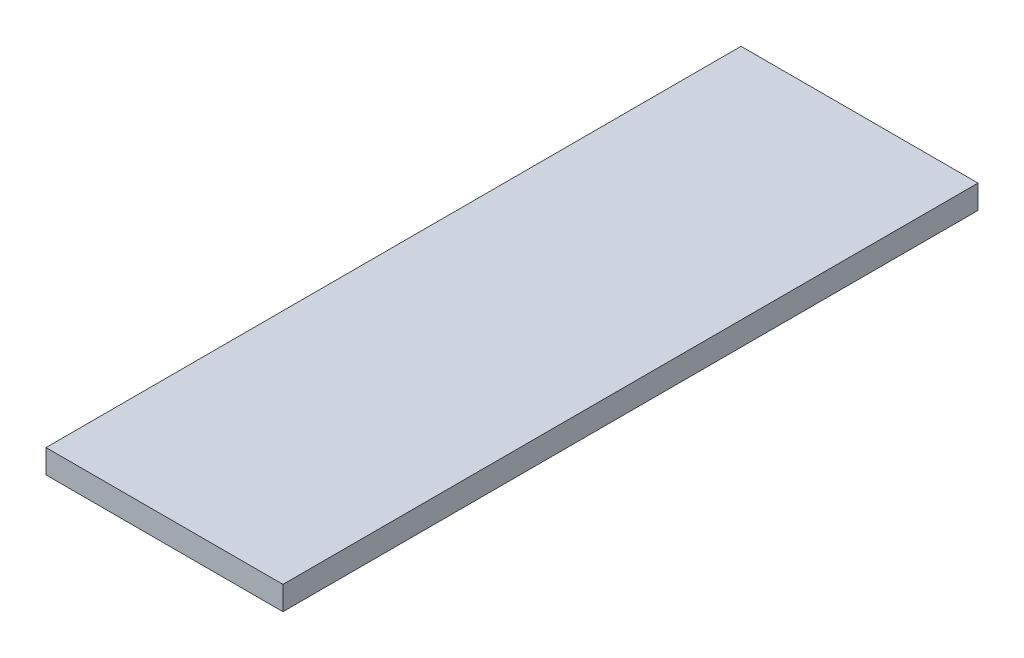
SolidWorks part; units mm, degrees
ref_plane "Front Plane" through (0, 0, 0) normal (0, 0, 1) x (1, 0, 0)
ref_plane "Top Plane" through (0, 0, 0) normal (0, 1, 0) x (1, 0, 0)
ref_plane "Right Plane" through (0, 0, 0) normal (1, 0, 0) x (0, 0, -1)
sketch "Sketch1" plane through (0, 0, 0) normal (0, 1, 0) x (1, 0, 0)
  line L1 (0, 0) -> (30, 0)
  line L2 (0, 0) -> (0, 88)
  line L3 (0, 88) -> (30, 88)
  line L4 (30, 0) -> (30, 88)
  dimension "D1" = 30
  dimension "D2" = 88
extrude "Boss-Extrude1" add sketch "Sketch1" along normal blind 3
